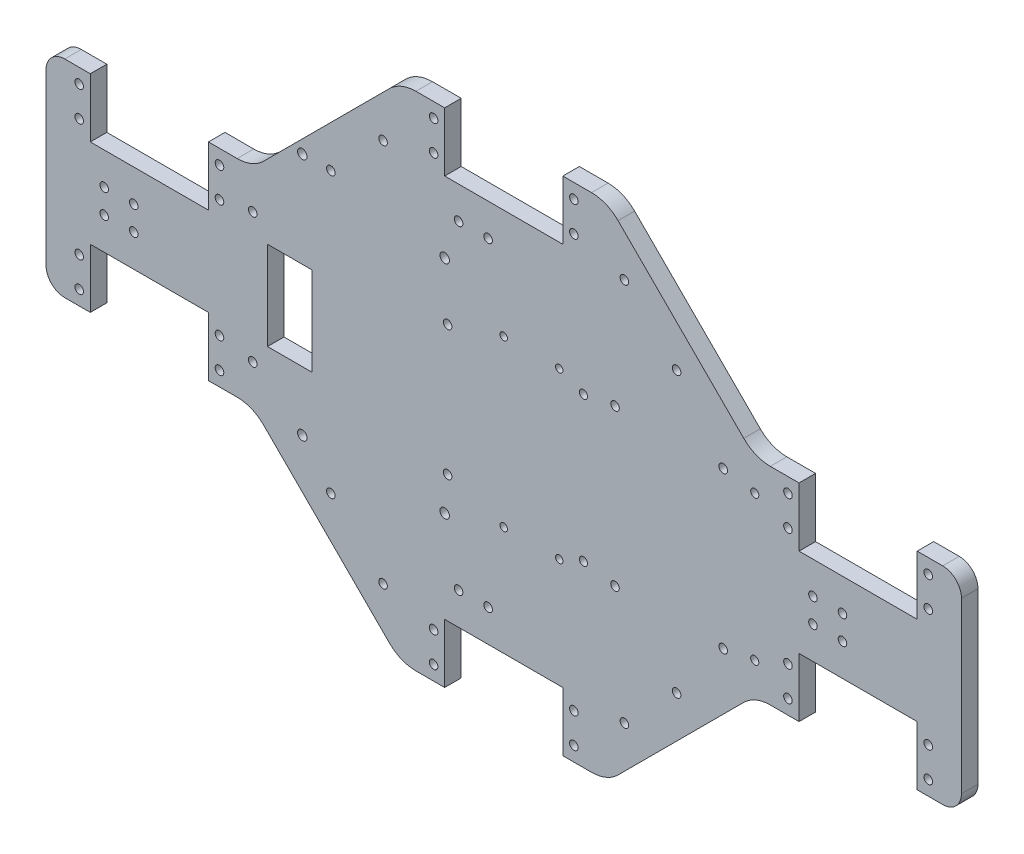
SolidWorks part; units mm, degrees
material "Acrylic (Medium-high impact)"
ref_plane "Front" through (0, 0, 0) normal (0, 0, 1) x (1, 0, 0)
ref_plane "Top" through (0, 0, 0) normal (0, 1, 0) x (1, 0, 0)
ref_plane "Right" through (0, 0, 0) normal (1, 0, 0) x (0, 0, -1)
sketch "Esquisse1" plane through (0, 0, 0) normal (0, 0, 1) x (1, 0, 0)
  line L0 (70, -35) -> (120, -85)
  line L1 (0, 0) -> (25.8386, 0)
  line L2 (0, 0) -> (0, -35)
  line L3 (0, -35) -> (70, -35)
  line L5 (0, 0) -> (70, -35) construction
  line L6 (0, -35) -> (25.8386, 0) construction
  line L7 (120, -85) -> (190, -85)
  line L8 (190, -85) -> (240, -35)
  line L9 (240, -35) -> (310, -35)
  line L10 (310, -35) -> (310, 0)
  line L11 (310, 0) -> (25.8386, 0)
  point P0 (0, 0)
  dimension "D1" = 70
  dimension "D2" = 70
  dimension "D3" = 70
  dimension "D4" = 135
  dimension "D5" = 135
  dimension "D6" = 0
  dimension "D7" = 50
  dimension "D8" = 35
extrude "Boss.-Extru.1" add sketch "Esquisse1" along normal blind 5.6
sketch "Esquisse2" plane through (0, 0, 5.6) normal (0, 0, 1) x (1, 0, 0)
  line L0 (0, -35) -> (70, -35) construction
  line L1 (15, -15) -> (55, -15)
  line L2 (15, -15) -> (15, -35)
  line L3 (15, -35) -> (55, -35)
  line L4 (55, -15) -> (55, -35)
  line L5 (15, -15) -> (55, -35) construction
  line L6 (15, -35) -> (55, -15) construction
  line L7 (0, 0) -> (0, -35) construction
  point P0 (0, -90)
  dimension "D1" = 20
  dimension "D2" = 40
  dimension "D3" = 15
extrude "Enlèv. mat.-Extru.1" cut sketch "Esquisse2" against normal up to next
sketch "Esquisse3" plane through (0, 0, 5.6) normal (0, 0, 1) x (1, 0, 0)
  line L0 (15, -25) -> (55, -25) construction
  line L1 (15, -15) -> (15, -35) construction
  line L2 (55, -35) -> (55, -15) construction
  circle A0 centre (11.25, -30.08) radius 1.45
  circle A1 centre (58.75, -30.08) radius 1.45
  circle A2 centre (58.75, -19.92) radius 1.45
  circle A3 centre (11.25, -19.92) radius 1.45
  circle A4 centre (19.712, -4.09) radius 1.45
  circle A5 centre (29.712, -4.09) radius 1.45
  dimension "D1" = 3.75
  dimension "D2" = 5.08
  dimension "D3" = 47.5
  dimension "D4" = 2.9
  dimension "D5" = 3.75
  dimension "D6" = 2.9
  dimension "D7" = 2.9
  dimension "D8" = 10
  dimension "D9" = 8.462
  dimension "D10" = 15.83
  dimension "D11" = 0
extrude "Enlèv. mat.-Extru.2" cut sketch "Esquisse3" against normal up to next
sketch "Sketch2" plane through (0, 0, 0) normal (0, 0, 1) x (1, 0, 0)
  line L0 (120, -85) -> (190, -85) construction
  line L1 (255, -15) -> (295, -15)
  line L2 (255, -15) -> (255, -35)
  line L3 (255, -35) -> (295, -35)
  line L4 (295, -15) -> (295, -35)
  line L5 (255, -15) -> (295, -35) construction
  line L6 (255, -35) -> (295, -15) construction
  line L7 (240, -35) -> (310, -35) construction
  line L8 (310, -35) -> (310, 0) construction
  line L9 (135, -65) -> (175, -65)
  line L10 (135, -65) -> (135, -85)
  line L11 (135, -85) -> (175, -85)
  line L12 (175, -65) -> (175, -85)
  line L13 (135, -65) -> (175, -85) construction
  line L14 (135, -85) -> (175, -65) construction
  point P0 (0, -90)
  point P11 (-35, 0)
  dimension "D1" = 20
  dimension "D2" = 40
  dimension "D3" = 15
  dimension "D4" = 40
  dimension "D5" = 20
  dimension "D6" = 15
extrude "Cut-Extrude2" cut sketch "Sketch2" against normal through all and the other way through all
sketch "Sketch5" plane through (0, 0, 0) normal (0, 0, 1) x (1, 0, 0)
  line L0 (180, -75) -> (175, -75) construction
  line L1 (175, -85) -> (175, -65) construction
  line L2 (255, -25) -> (295, -25) construction
  line L4 (295, -35) -> (295, -15) construction
  line L5 (255, -15) -> (255, -35) construction
  circle A0 centre (131.25, -80.08) radius 1.45
  circle A1 centre (178.75, -80.08) radius 1.45
  circle A2 centre (178.75, -69.92) radius 1.45
  circle A3 centre (131.25, -69.92) radius 1.45
  circle A4 centre (251.25, -30.08) radius 1.45
  circle A5 centre (298.75, -30.08) radius 1.45
  circle A6 centre (298.75, -19.92) radius 1.45
  circle A7 centre (251.25, -19.92) radius 1.45
  circle A8 centre (139.712, -54.09) radius 1.45
  circle A9 centre (149.712, -54.09) radius 1.45
  circle A10 centre (259.712, -4.09) radius 1.45
  circle A11 centre (269.712, -4.09) radius 1.45
  dimension "D1" = 5.08
  dimension "D2" = 5.08
  dimension "D3" = 47.5
  dimension "D4" = 2.9
  dimension "D5" = 3.75
  dimension "D10" = 2.9
  dimension "D11" = 2.9
  dimension "D12" = 2.9
  dimension "D16" = 2.9
  dimension "D17" = 2.9
  dimension "D6" = 5.08
  dimension "D7" = 5.08
  dimension "D8" = 3.75
  dimension "D9" = 3.75
  dimension "D13" = 10
  dimension "D14" = 8.462
  dimension "D15" = 15.83
  dimension "D18" = 8.462
  dimension "D19" = 15.83
  dimension "D20" = 10
  dimension "D21" = 0
  dimension "D22" = 0
extrude "Cut-Extrude4" cut sketch "Sketch5" along normal through all
mirror "Mirror1" about plane through (0, 0, 0) normal (0, 1, 0) of "Cut-Extrude4", "Cut-Extrude2", "Enlèv. mat.-Extru.1", "Enlèv. mat.-Extru.2", "Boss.-Extru.1"
sketch "Esquisse4" plane through (0, 0, 5.6) normal (0, 0, 1) x (1, 0, 0)
  line L0 (182, 24.5) -> (240, 24.5) construction
  line L1 (240, 24.5) -> (240, -24.5) construction
  line L2 (240, -24.5) -> (182, -24.5) construction
  line L3 (0, 0) -> (310, 0) construction
  line L4 (0, 35) -> (0, -35) construction
  line L5 (310, -35) -> (310, 35) construction
  line L6 (255, 15) -> (255, 35) construction
  circle A0 centre (182, -24.5) radius 1.375
  circle A4 centre (240, -24.5) radius 1.375
  circle A5 centre (240, 24.5) radius 1.375
  circle A6 centre (182, 24.5) radius 1.375
  point P14 (240, 0)
  dimension "D1" = 2.75
  dimension "D6" = 15
  dimension "D2" = 2
  dimension "D3" = 58
  dimension "D4" = 49
  dimension "D5" = 2
extrude "Enlèv. mat.-Extru.4" cut sketch "Esquisse4" against normal through all
sketch "Esquisse6" plane through (0, 0, 0) normal (0, 0, -1) x (-1, 0, 0)
  line L0 (0, 0) -> (-385.37, 0) construction
  line L1 (-229.315, 26.415) -> (-192.685, 26.415) construction
  line L2 (-192.685, 26.415) -> (-192.685, -26.415) construction
  line L3 (-192.685, -26.415) -> (-229.315, -26.415) construction
  line L4 (-182, 24.5) -> (-240, 24.5) construction
  line L5 (-211, 24.5) -> (-211, 26.415) construction
  circle A0 centre (-192.685, -26.415) radius 1.45
  circle A4 centre (-229.315, -26.415) radius 1.45
  circle A5 centre (-229.315, 26.415) radius 1.45
  circle A6 centre (-192.685, 26.415) radius 1.45
  point P5 (-192.685, 0)
  dimension "D1" = 2.9
  dimension "D2" = 2
  dimension "D3" = 36.63
  dimension "D4" = 52.83
  dimension "D5" = 2
extrude "Enlèv. mat.-Extru.6" cut sketch "Esquisse6" against normal through all
sketch "Esquisse8" plane through (0, 0, 0) normal (0, 0, -1) x (-1, 0, 0)
  line L0 (-173.8, 27.95) -> (-155, 27.95) construction
  line L1 (-155, 27.95) -> (-155, -27.95) construction
  line L2 (-155, -27.95) -> (-173.8, -27.95) construction
  line L3 (0, 0) -> (-310, 0) construction
  line L4 (-310, -35) -> (-310, 35) construction
  line L5 (-55, 35) -> (-55, 15) construction
  circle A0 centre (-155, 27.95) radius 1.25
  circle A1 centre (-173.8, 27.95) radius 1.25
  circle A2 centre (-173.8, -27.95) radius 1.25
  circle A3 centre (-155, -27.95) radius 1.25
  point P16 (-155, 0)
  dimension "D1" = 2.5
  dimension "D2" = 18.8
  dimension "D3" = 55.9
  dimension "D6" = 100
  dimension "D4" = 2
  dimension "D5" = 2
extrude "Enlèv. mat.-Extru.7" cut sketch "Esquisse8" against normal through all
sketch "Esquisse9" plane through (0, 0, 0) normal (0, 0, -1) x (-1, 0, 0)
  line L0 (-135, 65) -> (-135, 85) construction
  line L2 (-175, 65) -> (-135, 65) construction
  circle A1 centre (-135, -33.88) radius 1.6
  circle A2 centre (-86.78, -35.11) radius 1.6
  circle A3 centre (-86.78, 47.36) radius 1.6
  circle A4 centre (-135, 41) radius 1.6
  dimension "D8" = 1.23
  dimension "D1" = 74.88
  dimension "D2" = 82.47
  dimension "D3" = 48.22
  dimension "D4" = 48.22
  dimension "D5" = 48.22
  dimension "D6" = 24
extrude "Enlèv. mat.-Extru.8" cut sketch "Esquisse9" against normal through all
sketch "Sketch6" plane through (0, 0, 5.6) normal (0, 0, 1) x (1, 0, 0)
  line L0 (0, 0) -> (310, 0) construction
  line L1 (75, -15) -> (90, -15)
  line L2 (75, -15) -> (75, 15)
  line L3 (75, 15) -> (90, 15)
  line L4 (90, -15) -> (90, 15)
  line L5 (310, -35) -> (310, 35) construction
  line L6 (55, 15) -> (15, 15) construction
  line L7 (55, 35) -> (55, 15) construction
  point P9 (75, 0)
  dimension "D1" = 20
  dimension "D2" = 15
extrude "Cut-Extrude5" cut sketch "Sketch6" against normal blind 10
sketch "Sketch7" plane through (0, 0, 0) normal (0, 0, -1) x (-1, 0, 0)
  line L0 (0, 0) -> (-310, 0) construction
  line L1 (-70, 22) -> (-136, 22) construction
  line L2 (-70, 22) -> (-70, -22) construction
  line L3 (-70, -22) -> (-136, -22) construction
  line L4 (-136, 22) -> (-136, -22) construction
  line L5 (-70, 22) -> (-136, -22) construction
  line L6 (-70, -22) -> (-136, 22) construction
  line L7 (0, 35) -> (0, -35) construction
  line L8 (-310, -35) -> (-310, 35) construction
  line L10 (-75, 15) -> (-75, -15) construction
  circle A0 centre (-70, -22) radius 1.45
  circle A1 centre (-136, -22) radius 1.45
  circle A2 centre (-136, 22) radius 1.45
  circle A3 centre (-70, 22) radius 1.45
  point P4 (-103, 0)
  dimension "D1" = 2.9
  dimension "D2" = 66
  dimension "D3" = 44
  dimension "D4" = 5
extrude "Cut-Extrude6" cut sketch "Sketch7" against normal up to surface (5.6 mm away) up to face at (82.5, 0, 5.6)
ref_plane "Plan1" through (155, 0, 0) normal (-1, 0, 0) x (0, 0, 1)
ref_plane "Plan2" through (0, 0, 0) normal (0, 1, 0) x (1, 0, 0)
sketch "Esquisse12" plane through (0, 0, 5.6) normal (0, 0, 1) x (1, 0, 0)
  line L0 (96.4645, 47.3223) -> (114.1421, 65) construction
  line L1 (155, 24.0954) -> (155, -24.0954) construction
  line L2 (22.5792, 0) -> (-22.5792, 0) construction
  line L3 (70, 35) -> (120, 85) construction
  line L4 (175, 65) -> (135, 65) construction
  circle A0 centre (114.1421, 65) radius 1.45
  circle A1 centre (96.4645, 47.3223) radius 1.45
  circle A2 centre (213.5355, 47.3223) radius 1.45
  circle A3 centre (195.8579, 65) radius 1.45
  circle A4 centre (213.5355, -47.3223) radius 1.45
  circle A5 centre (195.8579, -65) radius 1.45
  circle A6 centre (114.1421, -65) radius 1.45
  circle A7 centre (96.4645, -47.3223) radius 1.45
  dimension "D1" = 2.9
  dimension "D2" = 2.9
  dimension "D3" = 25
  dimension "D4" = 10
extrude "Enlèv. mat.-Extru.11" cut sketch "Esquisse12" against normal through all
fillet "Fillet1" radius 6.35 4 edges at (310, 35, 2.8) (310, -35, 2.8) (0, -35, 2.8) (0, 35, 2.8)
fillet "Fillet2" radius 12.7 8 edges at (120, -85, 2.8) (70, -35, 2.8) (190, -85, 2.8) (240, -35, 2.8) (240, 35, 2.8) (190, 85, 2.8) (120, 85, 2.8) (70, 35, 2.8)
